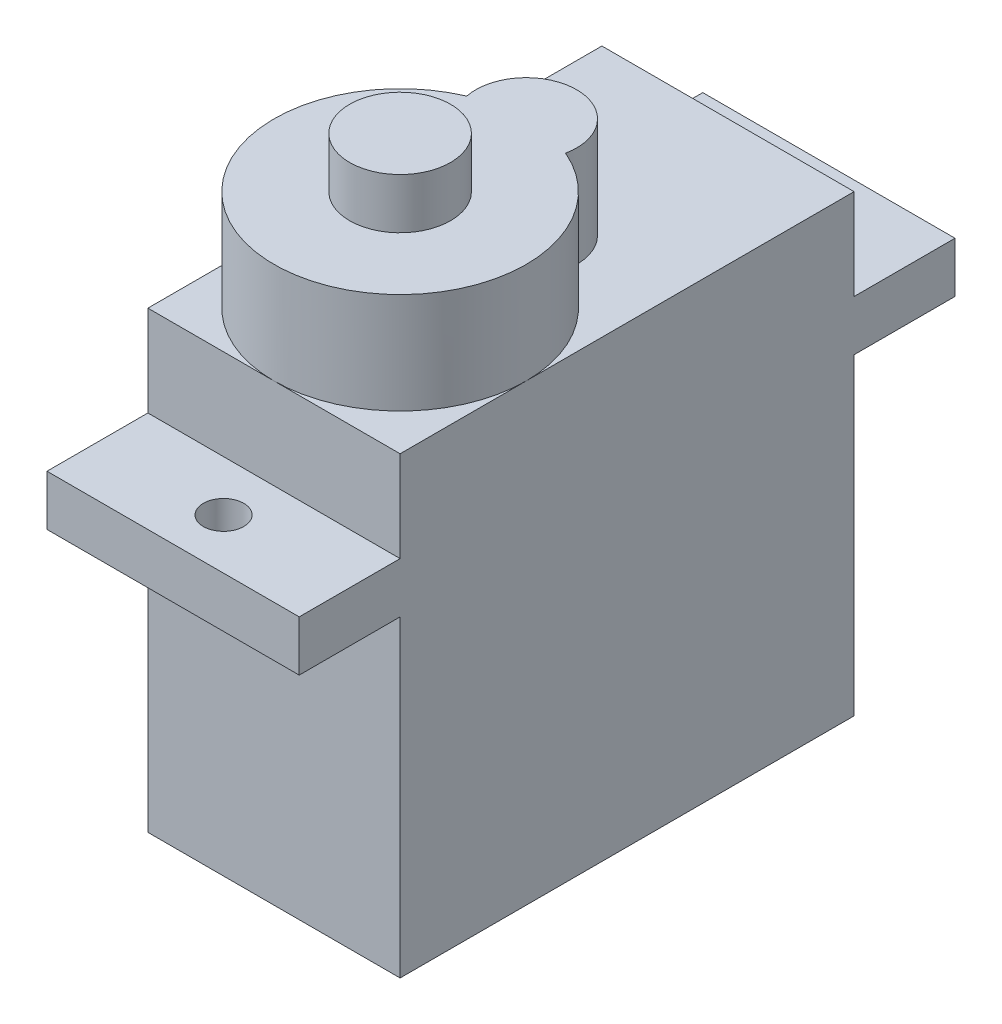
SolidWorks part; units mm, degrees
material "PVC Rigid"
ref_plane "Front Plane" through (0, 0, 0) normal (0, 0, 1) x (1, 0, 0)
ref_plane "Top Plane" through (0, 0, 0) normal (0, 1, 0) x (1, 0, 0)
ref_plane "Right Plane" through (0, 0, 0) normal (1, 0, 0) x (0, 0, -1)
sketch "Sketch1" plane through (0, 0, 0) normal (0, 0, 1) x (1, 0, 0)
  line L1 (0, 0) -> (12.5, 0)
  line L2 (0, 0) -> (0, 22.5)
  line L3 (0, 22.5) -> (12.5, 22.5)
  line L4 (12.5, 0) -> (12.5, 22.5)
  dimension "D1" = 12.5
  dimension "D2" = 22.5
extrude "Boss-Extrude1" add sketch "Sketch1" along normal blind 22.5
sketch "Sketch2" plane through (0, 0, 22.5) normal (0, 0, 1) x (1, 0, 0)
  line L0 (0, 22.5) -> (0, 0) construction
  line L1 (0, 15.5) -> (12.5, 15.5)
  line L2 (0, 15.5) -> (0, 18)
  line L3 (0, 18) -> (12.5, 18)
  line L4 (12.5, 15.5) -> (12.5, 18)
  line L5 (12.5, 0) -> (12.5, 22.5) construction
  line L6 (12.5, 22.5) -> (0, 22.5) construction
  dimension "D1" = 2.5
  dimension "D2" = 4.5
extrude "Boss-Extrude2" add sketch "Sketch2" along normal blind 5 and the other way blind 27.5
sketch "Sketch3" plane through (0, 22.5, 0) normal (0, 1, 0) x (1, 0, 0)
  line L0 (12.5, -22.5) -> (0, -22.5) construction
  arc A0 (3.8005, -10.5) -> (8.6995, -10.5) centre (6.25, -16.25) ccw
  arc A1 (8.6995, -10.5) -> (3.8005, -10.5) centre (6.25, -10) ccw
  dimension "D1" = 6.25
  dimension "D2" = 5
extrude "Boss-Extrude3" add sketch "Sketch3" along normal blind 5
sketch "Sketch4" plane through (0, 27.5, 0) normal (0, 1, 0) x (1, 0, 0)
  circle A0 centre (6.25, -16.25) radius 2.5
  dimension "D1" = 5
extrude "Boss-Extrude4" add sketch "Sketch4" along normal blind 2.5
sketch "Sketch5" plane through (0, 18, 0) normal (0, 1, 0) x (1, 0, 0)
  circle A0 centre (6.25, -25) radius 1
  circle A1 centre (6.25, 2.5) radius 1
  dimension "D1" = 2
  dimension "D2" = 2
extrude "Cut-Extrude1" cut sketch "Sketch5" against normal through all
